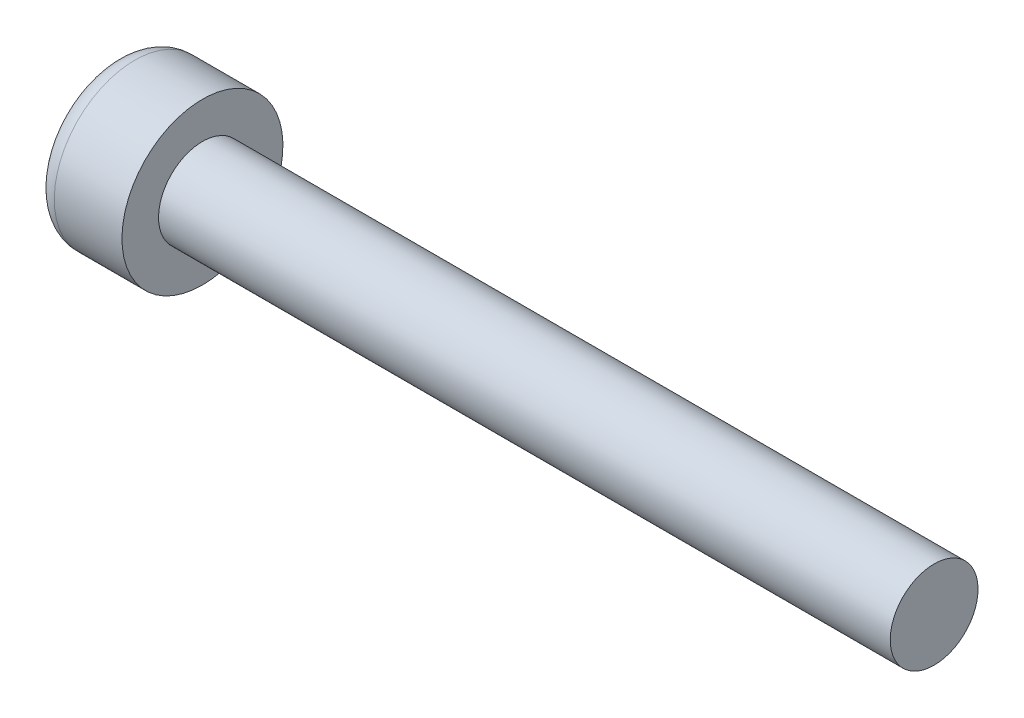
SolidWorks part; units mm, degrees
material "Plain Carbon Steel"
ref_plane "Front Plane" through (0, 0, 0) normal (0, 0, 1) x (1, 0, 0)
ref_plane "Top Plane" through (0, 0, 0) normal (0, 1, 0) x (1, 0, 0)
ref_plane "Right Plane" through (0, 0, 0) normal (1, 0, 0) x (0, 0, -1)
sketch "Sketch1" plane through (0, 0, 0) normal (0, 0, 1) x (1, 0, 0)
  line L0 (0, 0) -> (0, 2.0625)
  line L1 (0.6875, 2.75) -> (3, 2.75)
  line L2 (3, 2.75) -> (3, 1.5)
  line L3 (3, 1.5) -> (28, 1.5)
  line L4 (28, 1.5) -> (28, 0)
  line L5 (28, 0) -> (0, 0) construction
  line L6 (0.6875, 2.0625) -> (0.6875, 1.375) construction
  line L7 (0.6875, 1.375) -> (0.6875, 0.6875) construction
  line L8 (0.6875, 0.6875) -> (0.6875, 0) construction
  line L9 (0.6875, 2.75) -> (0.6875, 2.0625) construction
  line L10 (0, 0) -> (28, 0)
  arc A0 (0, 2.0625) -> (0.6875, 2.75) centre (0.6875, 2.0625) cw
  dimension "D1" = 3
  dimension "D2" = 5.5
  dimension "D3" = 3
  dimension "D4" = 25
revolve "Revolve1" add sketch "Sketch1" angle 360 about L10
sketch "Sketch2" plane through (0, 0, 0) normal (-1, 0, 0) x (0, 0, 1)
  line L1 (0, 1.4434) -> (-1.25, 0.7217)
  line L2 (-1.25, 0.7217) -> (-1.25, -0.7217)
  line L3 (-1.25, -0.7217) -> (0, -1.4434)
  line L4 (0, -1.4434) -> (1.25, -0.7217)
  line L5 (1.25, -0.7217) -> (1.25, 0.7217)
  line L6 (1.25, 0.7217) -> (0, 1.4434)
  circle A0 centre (0, 0) radius 1.25 construction
  dimension "D1" = 2.5
extrude "Cut-Extrude1" cut sketch "Sketch2" against normal blind 1.5
